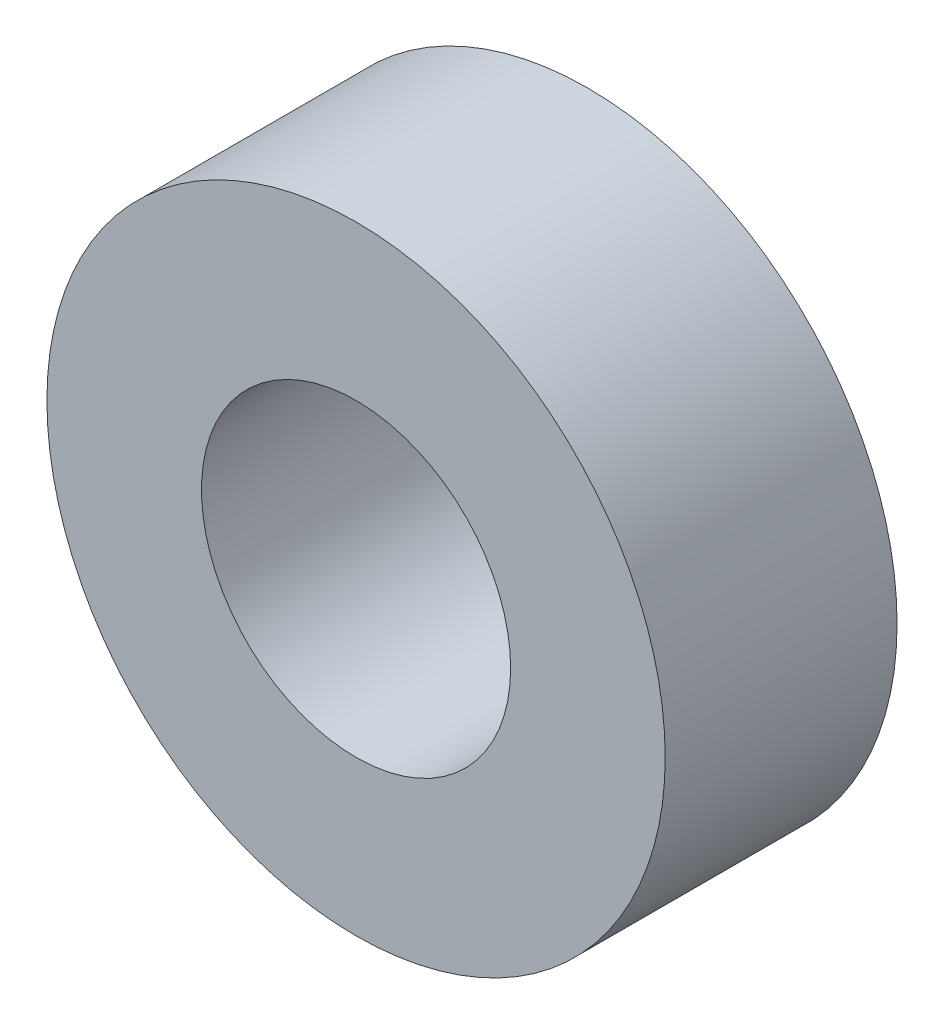
SolidWorks part; units mm, degrees
material "合金钢"
ref_plane "前视基准面" through (0, 0, 0) normal (0, 0, 1) x (1, 0, 0)
ref_plane "上视基准面" through (0, 0, 0) normal (0, 1, 0) x (1, 0, 0)
ref_plane "右视基准面" through (0, 0, 0) normal (1, 0, 0) x (0, 0, -1)
sketch "草图1" plane through (0, 0, 0) normal (0, 0, 1) x (1, 0, 0)
  circle A0 centre (0, 0) radius 4
  circle A1 centre (0, 0) radius 2
  dimension "D1" = 4
  dimension "D2" = 8
extrude "凸台-拉伸1" add sketch "草图1" along normal blind 3
